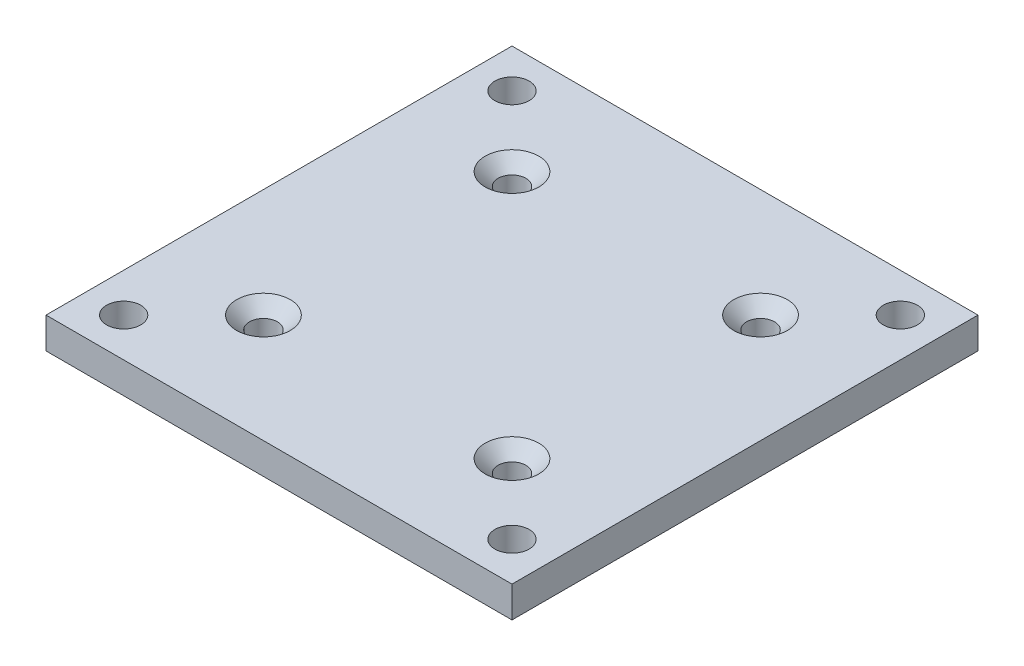
SolidWorks part; units mm, degrees
ref_plane "Front Plane" through (0, 0, 0) normal (0, 0, 1) x (1, 0, 0)
ref_plane "Top Plane" through (0, 0, 0) normal (0, 1, 0) x (1, 0, 0)
ref_plane "Right Plane" through (0, 0, 0) normal (1, 0, 0) x (0, 0, -1)
sketch "Sketch1" plane through (0, 0, 0) normal (0, 1, 0) x (1, 0, 0)
  line L0 (-30, 30) -> (0, 0) construction
  line L1 (-30, 30) -> (30, 30)
  line L2 (-30, 30) -> (-30, -30)
  line L3 (-30, -30) -> (30, -30)
  line L4 (30, 30) -> (30, -30)
  circle A0 centre (-25, 25) radius 2.2
  circle A1 centre (-16, 16) radius 1.65
  circle A2 centre (-25, -25) radius 2.2
  circle A3 centre (-16, -16) radius 1.65
  circle A4 centre (25, -25) radius 2.2
  circle A5 centre (16, -16) radius 1.65
  circle A6 centre (25, 25) radius 2.2
  circle A7 centre (16, 16) radius 1.65
  point P4 (0, 30)
  point P6 (30, 0)
  point P27 (0, 0)
  dimension "D5" = 3.3
  dimension "D6" = 4.4
  dimension "D1" = 60
  dimension "D2" = 60
  dimension "D3" = 25
  dimension "D4" = 16
  dimension "D7" = 4
extrude "Boss-Extrude1" add sketch "Sketch1" along normal blind 4
hole_wizard "CSK for M3 Flat Head Machine Screw1" positions "3DSketch1" profile "Sketch2" countersink size "M3" standard "ANSI Metric" end condition through all
sketch3d "3DSketch1"
  line L0 (16, 4, -16) -> (16, 0, -16) construction
  line L1 (16, 4, 16) -> (16, 0, 16) construction
  line L2 (-16, 4, 16) -> (-16, 0, 16) construction
  line L3 (-16, 4, -16) -> (-16, 0, -16) construction
  point P0 (16, 4, -16)
  point P4 (16, 4, 16)
  point P8 (-16, 4, 16)
  point P12 (-16, 4, -16)
sketch "Sketch2" plane through (16, 4, -16) normal (1, 0, 0) x (0, 0, 1)
  line L0 (0, 0) -> (0, 4)
  line L1 (0, 4) -> (1.8, 4)
  line L2 (1.8, 4) -> (1.8, 1.65)
  line L3 (1.8, 1.65) -> (3.45, 0)
  line L5 (3.45, 0) -> (0, 0)
  line L6 (-1.8, 1.65) -> (-3.45, 0) construction
  line L11 (0, -6.35) -> (0, 107.95) construction
  dimension "Thru Hole Dia." = 3.6
  dimension "Thru Hole Depth" = 4
  dimension "Near C'Sink Dia." = 6.9
  dimension "Near C'Sink Angle" = 90
